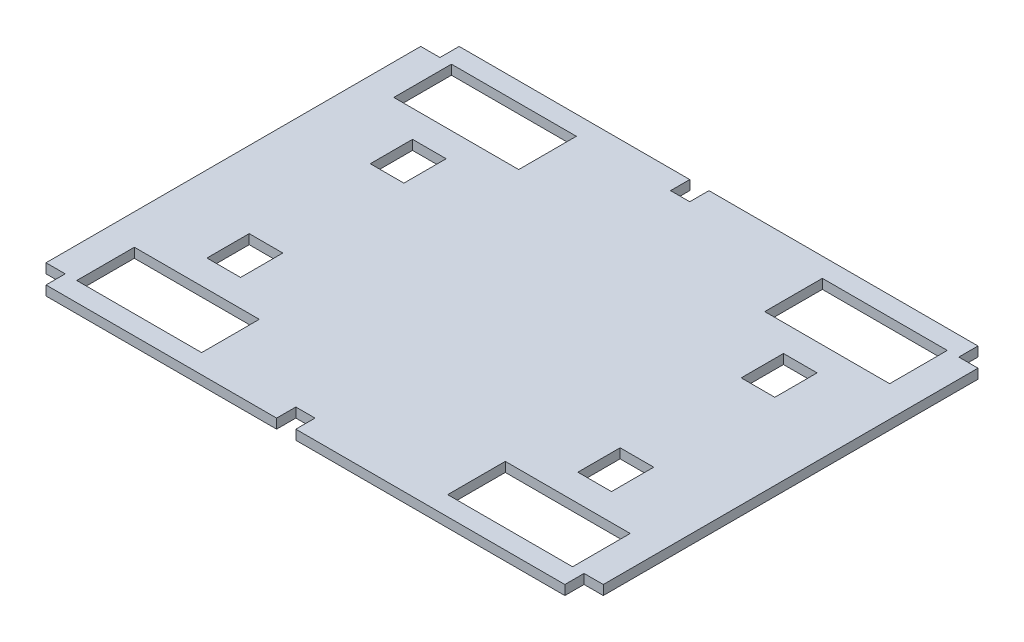
SolidWorks part; units mm, degrees
material "Maple"
ref_plane "Front Plane" through (0, 0, 0) normal (0, 0, 1) x (1, 0, 0)
ref_plane "Top Plane" through (0, 0, 0) normal (0, 1, 0) x (1, 0, 0)
ref_plane "Right Plane" through (0, 0, 0) normal (1, 0, 0) x (0, 0, -1)
sketch "Sketch1" plane through (0, 0, 0) normal (0, 1, 0) x (1, 0, 0)
  line L0 (0, 0) -> (-263.0233, 0) construction
  line L1 (-290, 215) -> (290, 215)
  line L2 (-290, 215) -> (-290, -215)
  line L3 (-290, -215) -> (290, -215)
  line L4 (290, 215) -> (290, -215)
  line L5 (-290, 215) -> (290, -215) construction
  line L6 (-290, -215) -> (290, 215) construction
  line L7 (-263.0233, 195) -> (263.0233, 195) construction
  line L8 (-263.0233, 195) -> (-263.0233, -195) construction
  line L9 (-263.0233, -195) -> (263.0233, -195) construction
  line L10 (263.0233, 195) -> (263.0233, -195) construction
  line L11 (-263.0233, 195) -> (263.0233, -195) construction
  line L12 (-263.0233, -195) -> (263.0233, 195) construction
  line L13 (-258.0233, 195) -> (-128.0233, 195)
  line L14 (-258.0233, 195) -> (-258.0233, 135)
  line L15 (-258.0233, 135) -> (-128.0233, 135)
  line L16 (-128.0233, 195) -> (-128.0233, 135)
  line L17 (-258.0233, 195) -> (-128.0233, 135) construction
  line L18 (-258.0233, 135) -> (-128.0233, 195) construction
  line L19 (-258.0233, -135) -> (-128.0233, -135)
  line L20 (-128.0233, -195) -> (-128.0233, -135)
  line L21 (-258.0233, -195) -> (-128.0233, -195)
  line L22 (-258.0233, -195) -> (-258.0233, -135)
  line L23 (-210.5233, -63) -> (-175.5233, -63)
  line L24 (-210.5233, 107) -> (-175.5233, 107)
  line L25 (-210.5233, 107) -> (-210.5233, 63)
  line L26 (-210.5233, 63) -> (-175.5233, 63)
  line L27 (-175.5233, 107) -> (-175.5233, 63)
  line L28 (-210.5233, 107) -> (-175.5233, 63) construction
  line L29 (-210.5233, 63) -> (-175.5233, 107) construction
  line L30 (-175.5233, -107) -> (-175.5233, -63)
  line L31 (-210.5233, -107) -> (-175.5233, -107)
  line L32 (-210.5233, -107) -> (-210.5233, -63)
  point P0 (0, 0)
  point P6 (0, 0)
  point P11 (-193.0233, 165)
  point P22 (-193.0233, 85)
  dimension "D1" = 580
  dimension "D2" = 430
  dimension "D3" = 20
  dimension "D4" = 10
  dimension "D5" = 130
  dimension "D6" = 60
  dimension "D7" = 35
  dimension "D8" = 44
  dimension "D9" = 28
extrude "Boss-Extrude1" add sketch "Sketch1" along normal mid plane 10
sketch "Sketch2" plane through (0, 5, 0) normal (0, 1, 0) x (1, 0, 0)
  line L0 (-290, 195) -> (-270, 195)
  line L1 (-290, 215) -> (-290, -215) construction
  line L2 (-270, 195) -> (-270, 215)
  line L3 (290, 215) -> (-290, 215) construction
  line L4 (-270, 215) -> (-290, 215)
  line L5 (-290, 215) -> (-290, 195)
  line L6 (0, 0) -> (-290, 0) construction
  line L7 (0, 0) -> (0, 215) construction
  line L8 (270, 215) -> (290, 215)
  line L9 (270, 195) -> (270, 215)
  line L10 (290, 195) -> (270, 195)
  line L11 (290, 215) -> (290, 195)
  line L12 (270, -195) -> (270, -215)
  line L13 (290, -195) -> (270, -195)
  line L14 (290, -215) -> (290, -195)
  line L15 (270, -215) -> (290, -215)
  line L16 (-270, -215) -> (-290, -215)
  line L17 (-270, -195) -> (-270, -215)
  line L18 (-290, -195) -> (-270, -195)
  line L19 (-290, -215) -> (-290, -195)
  dimension "D1" = 20
  dimension "D2" = 20
extrude "Cut-Extrude1" cut sketch "Sketch2" against normal blind 10 contours L5 L0 L2 L4 | L8 L11 L10 L9 | L12 L15 L14 L13 | L16 L19 L18 L17
sketch "Sketch3" plane through (0, 5, 0) normal (0, 1, 0) x (1, 0, 0)
  line L0 (0, 215) -> (0, -215) construction
  line L1 (270, 215) -> (-270, 215) construction
  line L2 (-270, -215) -> (270, -215) construction
  line L3 (128.0233, -195) -> (128.0233, -135)
  line L4 (258.0233, -195) -> (128.0233, -195)
  line L5 (258.0233, -135) -> (258.0233, -195)
  line L6 (128.0233, -135) -> (258.0233, -135)
  line L7 (-128.0233, 195) -> (-258.0233, 195)
  line L8 (-128.0233, 135) -> (-128.0233, 195)
  line L9 (-258.0233, 135) -> (-128.0233, 135)
  line L10 (-258.0233, 195) -> (-258.0233, 135)
  line L11 (-128.0233, 195) -> (-258.0233, 195)
  line L12 (-128.0233, 135) -> (-128.0233, 195)
  line L13 (-258.0233, 135) -> (-128.0233, 135)
  line L14 (-258.0233, 195) -> (-258.0233, 135)
  line L15 (175.5233, -107) -> (175.5233, -63)
  line L16 (210.5233, -107) -> (175.5233, -107)
  line L18 (210.5233, -63) -> (210.5233, -107)
  line L23 (-175.5233, 107) -> (-210.5233, 107)
  line L24 (-175.5233, 63) -> (-175.5233, 107)
  line L25 (-210.5233, 63) -> (-175.5233, 63)
  line L26 (-210.5233, 107) -> (-210.5233, 63)
  line L27 (-175.5233, 107) -> (-210.5233, 107)
  line L28 (-175.5233, 63) -> (-175.5233, 107)
  line L29 (-210.5233, 63) -> (-175.5233, 63)
  line L30 (-210.5233, 107) -> (-210.5233, 63)
  line L31 (-175.5233, -63) -> (-210.5233, -63)
  line L32 (-175.5233, -107) -> (-175.5233, -63)
  line L33 (-210.5233, -107) -> (-175.5233, -107)
  line L34 (-210.5233, -63) -> (-210.5233, -107)
  line L35 (-175.5233, -63) -> (-210.5233, -63)
  line L36 (-175.5233, -107) -> (-175.5233, -63)
  line L37 (-210.5233, -107) -> (-175.5233, -107)
  line L38 (-210.5233, -63) -> (-210.5233, -107)
  line L39 (-128.0233, -135) -> (-258.0233, -135)
  line L40 (-128.0233, -195) -> (-128.0233, -135)
  line L41 (-258.0233, -195) -> (-128.0233, -195)
  line L42 (-258.0233, -135) -> (-258.0233, -195)
  line L43 (-128.0233, -135) -> (-258.0233, -135)
  line L44 (-128.0233, -195) -> (-128.0233, -135)
  line L45 (-258.0233, -195) -> (-128.0233, -195)
  line L46 (-258.0233, -135) -> (-258.0233, -195)
  line L47 (175.5233, -63) -> (210.5233, -63)
  line L48 (175.5233, 63) -> (175.5233, 107)
  line L49 (210.5233, 63) -> (175.5233, 63)
  line L50 (210.5233, 107) -> (210.5233, 63)
  line L51 (175.5233, 107) -> (210.5233, 107)
  line L52 (128.0233, 135) -> (128.0233, 195)
  line L53 (258.0233, 135) -> (128.0233, 135)
  line L54 (258.0233, 195) -> (258.0233, 135)
  line L55 (128.0233, 195) -> (258.0233, 195)
  dimension "D1" = 0
  dimension "D3" = 0
  dimension "D4" = 0
  dimension "D5" = 0
extrude "Cut-Extrude2" cut sketch "Sketch3" against normal blind 98
sketch "Sketch4" plane through (0, 5, 0) normal (0, 1, 0) x (1, 0, 0)
  line L0 (-10, 215) -> (-10, -215) construction
  line L1 (270, 215) -> (-270, 215) construction
  line L2 (-270, -215) -> (270, -215) construction
  line L3 (290, -195) -> (290, 195) construction
  line L4 (-10, -215) -> (-10, -195)
  line L5 (-10, -195) -> (-30, -195)
  line L6 (-30, -195) -> (-30, -215)
  line L7 (-30, -215) -> (-10, -215)
  line L8 (-10, 0) -> (290, 0) construction
  line L9 (-30, 195) -> (-30, 215)
  line L10 (-10, 195) -> (-30, 195)
  line L11 (-10, 215) -> (-10, 195)
  line L12 (-30, 215) -> (-10, 215)
  dimension "D1" = 300
  dimension "D2" = 20
  dimension "D3" = 20
extrude "Cut-Extrude3" cut sketch "Sketch4" against normal blind 98
